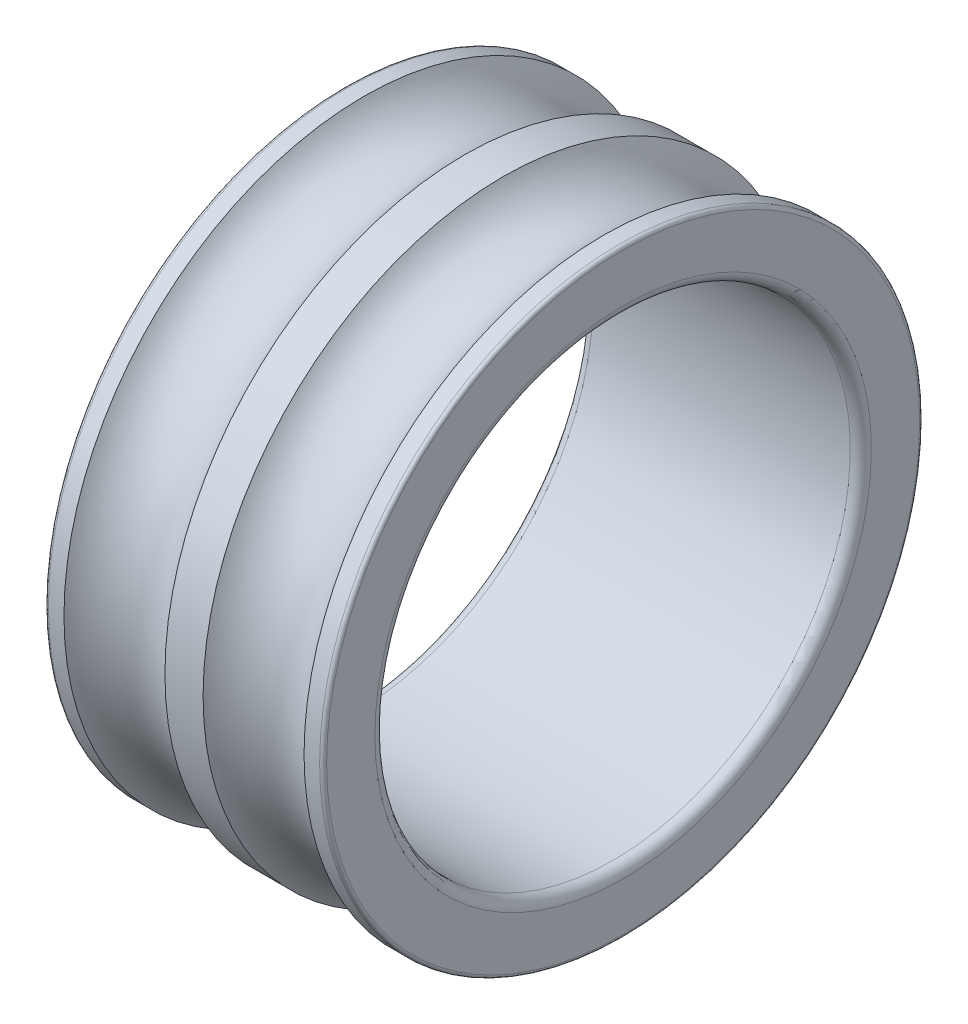
SolidWorks part; units mm, degrees
ref_plane "Piano frontale" through (0, 0, 0) normal (0, 0, 1) x (1, 0, 0)
ref_plane "Piano superiore" through (0, 0, 0) normal (0, 1, 0) x (1, 0, 0)
ref_plane "Piano destro" through (0, 0, 0) normal (1, 0, 0) x (0, 0, -1)
ref_plane "Piano1" through (0, 0, 0) normal (0, 0, 1) x (1, 0, 0)
sketch "Schizzo1" plane through (0, 0, 0) normal (0, 0, 1) x (1, 0, 0)
  line L0 (2.1, 47.5) -> (53.5, 47.5)
  line L1 (55.6, 49.6) -> (55.6, 59.25)
  line L2 (54.9, 59.95) -> (51.787, 59.95)
  line L3 (31.613, 59.95) -> (23.987, 59.95)
  line L4 (3.813, 59.95) -> (0.7, 59.95)
  line L5 (0, 59.25) -> (0, 49.6)
  line L6 (55.6, 0) -> (0, 0) construction
  arc A0 (0, 49.6) -> (2.1, 47.5) centre (2.1, 49.6) ccw
  arc A1 (53.5, 47.5) -> (55.6, 49.6) centre (53.5, 49.6) ccw
  arc A2 (55.6, 59.25) -> (54.9, 59.95) centre (54.9, 59.25) ccw
  arc A3 (51.787, 59.95) -> (31.613, 59.95) centre (41.7, 66.275) cw
  arc A4 (23.987, 59.95) -> (3.813, 59.95) centre (13.9, 66.275) cw
  arc A5 (0.7, 59.95) -> (0, 59.25) centre (0.7, 59.25) ccw
revolve "Rivoluzione1" add sketch "Schizzo1" angle 360 about L6
